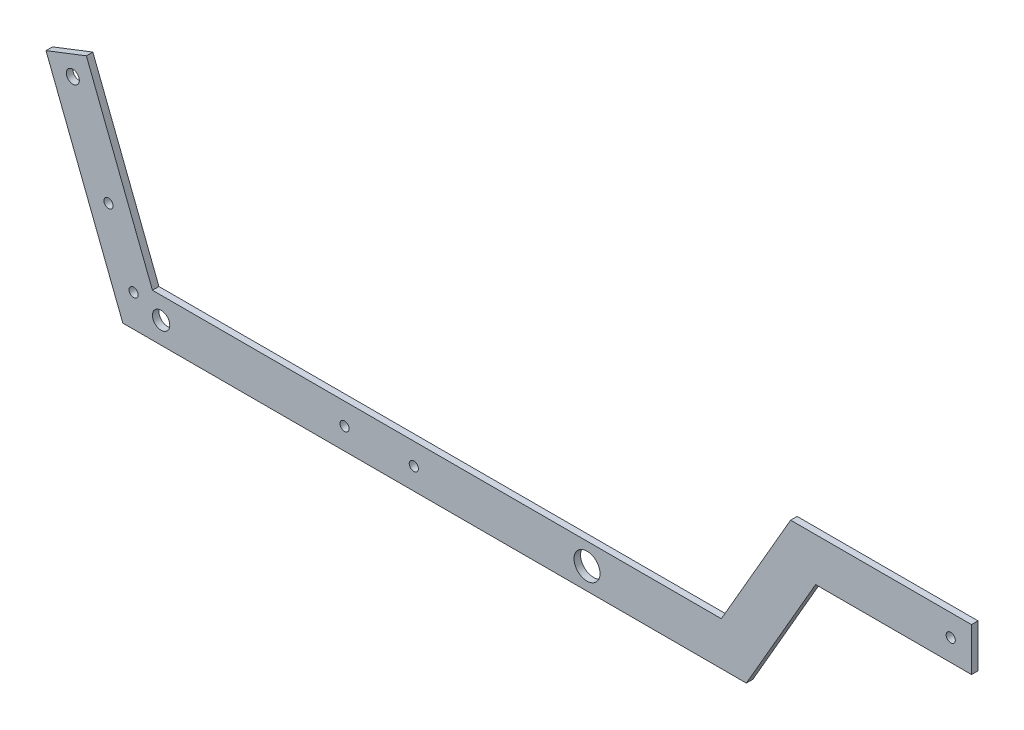
SolidWorks part; units mm, degrees
ref_plane "Front Plane" through (0, 0, 0) normal (0, 0, 1) x (1, 0, 0)
ref_plane "Top Plane" through (0, 0, 0) normal (0, 1, 0) x (1, 0, 0)
ref_plane "Right Plane" through (0, 0, 0) normal (1, 0, 0) x (0, 0, -1)
sketch "Sketch1" plane through (0, 0, 0) normal (0, 0, 1) x (1, 0, 0)
  line L0 (0, 0) -> (25.4, 43.9941)
  line L1 (-228.6, 0) -> (0, 0)
  line L2 (-228.6, 0) -> (-256.7651, 72.4489)
  line L3 (-217.7391, 15.875) -> (-9.1654, 15.875)
  line L4 (25.4, 43.9941) -> (82.55, 43.9941)
  line L5 (82.55, 43.9941) -> (82.55, 59.8691)
  line L6 (82.55, 59.8691) -> (16.2346, 59.8691)
  line L7 (16.2346, 59.8691) -> (-9.1654, 15.875)
  line L8 (-256.7651, 72.4489) -> (-241.9689, 78.201)
  line L9 (-241.9689, 78.201) -> (-217.7391, 15.875)
  circle A0 centre (-58.42, 7.9375) radius 4.7625
  dimension "D4" = 9.525
  dimension "D2" = 228.6
  dimension "D3" = 50.8
  dimension "D5" = 120
  dimension "D6" = 15.875
  dimension "D7" = 15.875
  dimension "D8" = 7.9375
  dimension "D9" = 15.875
  dimension "D10" = 15.875
  dimension "D11" = 57.15
  dimension "D12" = 58.42
extrude "Boss-Extrude1" add sketch "Sketch1" along normal blind 2.3813
sketch "Sketch4" plane through (0, 0, 2.3813) normal (0, 0, 1) x (1, 0, 0)
  line L0 (82.55, 51.9316) -> (74.93, 51.9316) construction
  line L1 (82.55, 43.9941) -> (82.55, 59.8691) construction
  line L2 (74.93, 51.9316) -> (-58.42, 7.9375) construction
  line L3 (-58.42, 7.9375) -> (74.93, 7.9375) construction
  line L4 (74.93, 7.9375) -> (74.93, 51.9316) construction
  line L5 (-241.9689, 78.201) -> (-217.7391, 15.875) construction
  circle A0 centre (74.93, 51.9316) radius 1.6764
  circle A1 centre (-58.42, 7.9375) radius 4.7625 construction
  circle A2 centre (-246.9376, 69.0758) radius 2.3813
  dimension "D1" = 3.3528
  dimension "D2" = 133.35
  dimension "D3" = 4.7625
  dimension "D4" = 7.9375
extrude "Cut-Extrude2" cut sketch "Sketch4" against normal through all
sketch "Sketch5" plane through (0, 0, 2.3813) normal (0, 0, 1) x (1, 0, 0)
  line L0 (0, 0) -> (0, 15.875) construction
  line L1 (-9.1654, 15.875) -> (9.1654, 15.875) construction
  line L2 (0, 0) -> (25.4, 43.9941) construction
  line L3 (-217.7391, 15.875) -> (-234.7715, 15.875) construction
  line L4 (-228.6, 0) -> (-256.7651, 72.4489) construction
  line L5 (-228.6, 0) -> (-228.6, 15.875) construction
  line L6 (-228.6, 7.9375) -> (0, 7.9375) construction
  line L7 (-241.9689, 78.201) -> (-217.7391, 15.875) construction
  line L8 (-249.367, 75.325) -> (-221.2019, 2.8761) construction
  line L9 (-256.7651, 72.4489) -> (-241.9689, 78.201) construction
  line L10 (-217.7391, 15.875) -> (-211.5676, 0) construction
  line L11 (-228.6, 0) -> (0, 0) construction
  line L12 (-228.6, 0) -> (-213.8038, 5.7522) construction
  circle A0 centre (-147.32, 7.9375) radius 1.6764
  circle A1 centre (-121.92, 7.9375) radius 1.6764
  circle A2 centre (-58.42, 7.9375) radius 4.7625 construction
  circle A3 centre (-224.6532, 11.7538) radius 1.6764
  circle A4 centre (-233.8566, 35.4278) radius 1.6764
  dimension "D1" = 3.3528
  dimension "D2" = 25.4
  dimension "D3" = 63.5
  dimension "D5" = 25.4
  dimension "D6" = 9.525
extrude "Cut-Extrude3" cut sketch "Sketch5" against normal through all
sketch "Sketch6" plane through (0, 0, 2.3813) normal (0, 0, 1) x (1, 0, 0)
  line L0 (-9.1654, 15.875) -> (-9.1654, 0) construction
  line L1 (-228.6, 0) -> (0, 0) construction
  line L2 (-217.7391, 15.875) -> (-217.7391, 0) construction
  circle A0 centre (-214.5641, 7.9375) radius 3.175
  point P2 (-9.1654, 7.9375)
  dimension "D1" = 6.35
  dimension "D2" = 3.175
extrude "Cut-Extrude4" cut sketch "Sketch6" against normal through all
